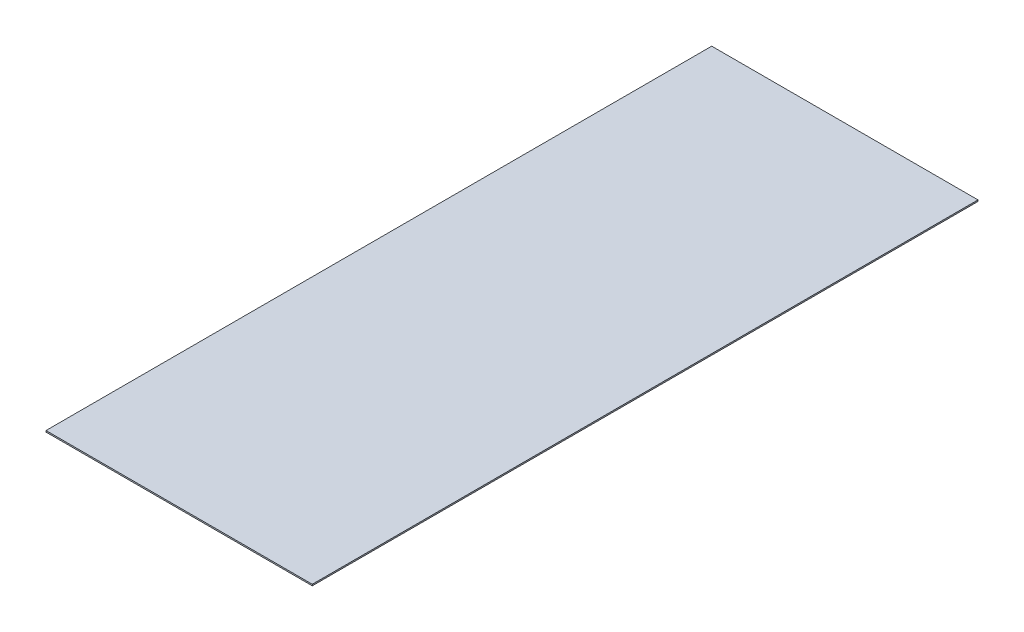
SolidWorks part; units mm, degrees
material "ASTM A36 Acero"
ref_plane "Alzado" through (0, 0, 0) normal (0, 0, 1) x (1, 0, 0)
ref_plane "Planta" through (0, 0, 0) normal (0, 1, 0) x (1, 0, 0)
ref_plane "Vista lateral" through (0, 0, 0) normal (1, 0, 0) x (0, 0, -1)
sketch "Croquis1" plane through (0, 0, 0) normal (0, 1, 0) x (1, 0, 0)
  line L1 (-609.6, -1524) -> (609.6, -1524)
  line L2 (-609.6, -1524) -> (-609.6, 1524)
  line L3 (-609.6, 1524) -> (609.6, 1524)
  line L4 (609.6, -1524) -> (609.6, 1524)
  line L5 (-609.6, -1524) -> (609.6, 1524) construction
  line L6 (-609.6, 1524) -> (609.6, -1524) construction
  point P0 (0, 0)
  dimension "D1" = 3048
  dimension "D2" = 1219.2
extrude "Saliente-Extruir1" add sketch "Croquis1" along normal blind 6.4
